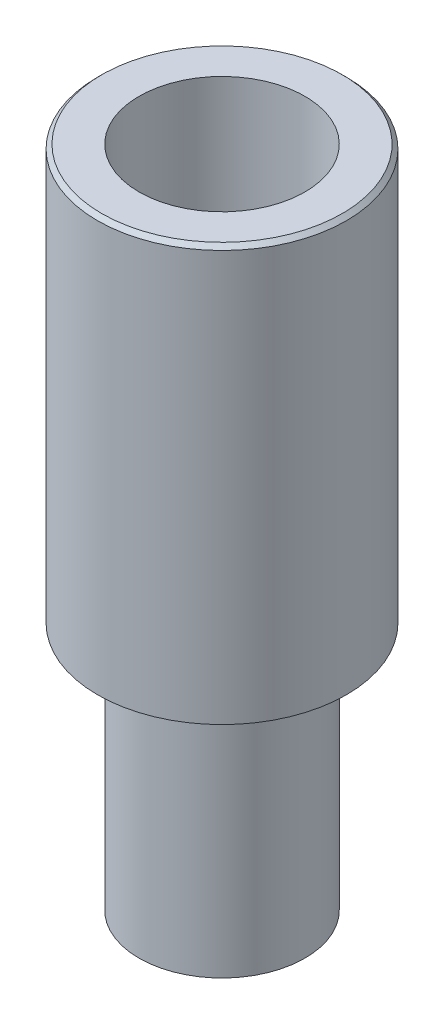
SolidWorks part; units mm, degrees
ref_plane "Front Plane" through (0, 0, 0) normal (0, 0, 1) x (1, 0, 0)
ref_plane "Top Plane" through (0, 0, 0) normal (0, 1, 0) x (1, 0, 0)
ref_plane "Right Plane" through (0, 0, 0) normal (1, 0, 0) x (0, 0, -1)
sketch "Sketch1" plane through (0, 0, 0) normal (0, 1, 0) x (1, 0, 0)
  circle A0 centre (0, 0) radius 2
  dimension "D1" = 4
extrude "Boss-Extrude1" add sketch "Sketch1" along normal blind 6
sketch "Sketch2" plane through (0, 6, 0) normal (0, 1, 0) x (1, 0, 0)
  circle A0 centre (0, 0) radius 3
  dimension "D1" = 6
extrude "Boss-Extrude2" add sketch "Sketch2" along normal blind 10
sketch "Sketch3" plane through (0, 16, 0) normal (0, 1, 0) x (1, 0, 0)
  circle A0 centre (0, 0) radius 2
  dimension "D1" = 4
extrude "Cut-Extrude1" cut sketch "Sketch3" against normal blind 6
chamfer "Chamfer1" distance 0.1 angle 45 1 edges at (0, 16, 3)
